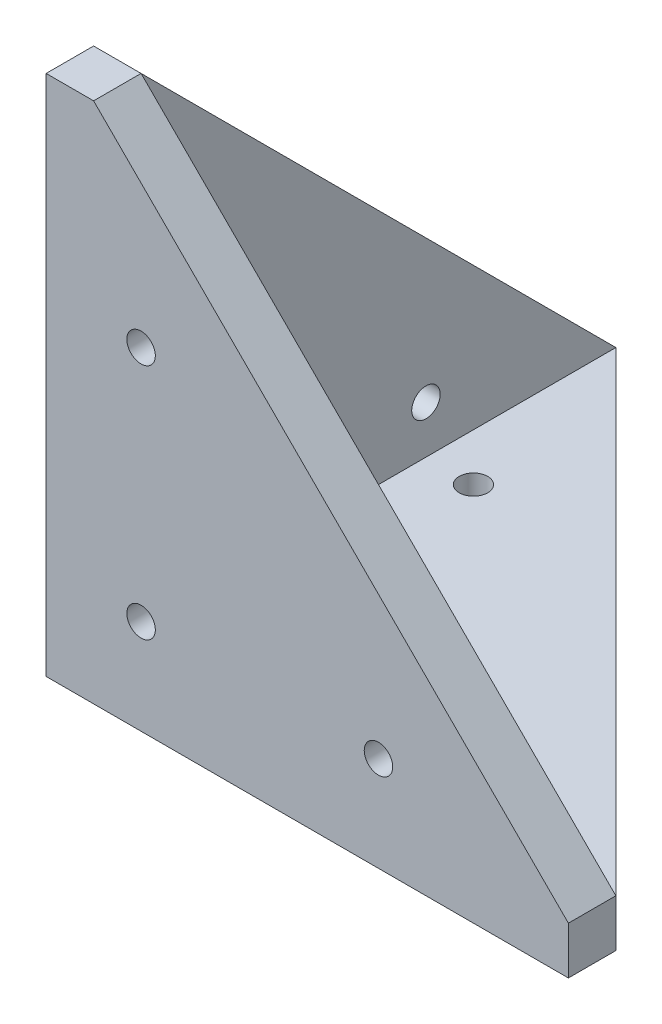
SolidWorks part; units mm, degrees
ref_plane "前视基准面" through (0, 0, 0) normal (0, 0, 1) x (1, 0, 0)
ref_plane "上视基准面" through (0, 0, 0) normal (0, 1, 0) x (1, 0, 0)
ref_plane "右视基准面" through (0, 0, 0) normal (1, 0, 0) x (0, 0, -1)
sketch "草图1" plane through (0, 0, 0) normal (0, 0, 1) x (1, 0, 0)
  line L5 (0, 50) -> (50, 0)
  line L6 (0, 50) -> (-5, 50)
  line L7 (-5, 50) -> (-5, -5)
  line L8 (-5, -5) -> (50, -5)
  line L9 (50, -5) -> (50, 0)
  dimension "D1" = 55
  dimension "D2" = 55
  dimension "D3" = 5
  dimension "D4" = 5
extrude "凸台-拉伸1" add sketch "草图1" along normal blind 5
sketch "草图2" plane through (0, 0, 0) normal (1, 0, 0) x (0, 0, -1)
  line L0 (0, 0) -> (50, 0)
  line L1 (50, 0) -> (0, 50)
  line L2 (0, 50) -> (0, 0)
  dimension "D1" = 50
  dimension "D2" = 50
extrude "凸台-拉伸2" add sketch "草图2" against normal blind 5 separate body
sketch "草图4" plane through (0, 0, 0) normal (0, 0, 1) x (1, 0, 0)
  line L1 (-5, 0) -> (0, 0)
  line L2 (-5, 0) -> (-5, -5)
  line L3 (-5, -5) -> (0, -5)
  line L4 (0, 0) -> (0, -5)
extrude "凸台-拉伸4" add sketch "草图4" against normal blind 50
sketch "草图7" plane through (0, -5, 0) normal (0, -1, 0) x (1, 0, 0)
  line L0 (50, 0) -> (0, 0)
  line L1 (0, 0) -> (0, -50)
  line L2 (0, -50) -> (50, 0)
  dimension "D1" = 50
extrude "凸台-拉伸13" add sketch "草图7" against normal blind 5
sketch "草图8" plane through (0, 0, 0) normal (1, 0, 0) x (0, 0, -1)
  line L0 (0, 0) -> (50, 0) construction
  line L2 (5, 30) -> (5, 5) construction
  line L3 (5, 5) -> (30, 5) construction
  line L5 (5, 30) -> (30, 5) construction
  line L7 (0, 0) -> (0, 50) construction
  circle A0 centre (5, 30) radius 1.5
  circle A1 centre (5, 5) radius 1.4
  circle A2 centre (30, 5) radius 1.5
  point P0 (18.9005, 16.0995)
  dimension "D1" = 25
  dimension "D2" = 25
  dimension "D3" = 5
  dimension "D4" = 5
extrude "切除-拉伸1" cut sketch "草图8" against normal through all
sketch "草图9" plane through (0, 0, 0) normal (0, 0, -1) x (-1, 0, 0)
  line L0 (0, 0) -> (0, 50) construction
  line L1 (-30, 5) -> (-5, 5) construction
  line L4 (-5, 5) -> (-5, 30) construction
  line L5 (-30, 5) -> (-5, 30) construction
  line L7 (-50, 0) -> (0, 0) construction
  circle A0 centre (-5, 30) radius 1.5
  circle A1 centre (-5, 5) radius 1.5
  circle A2 centre (-30, 5) radius 1.5
  point P0 (-20.4255, 14.5745)
  dimension "D1" = 25
  dimension "D2" = 25
  dimension "D3" = 5
  dimension "D4" = 5
extrude "切除-拉伸2" cut sketch "草图9" against normal through all
sketch "草图10" plane through (0, 0, 0) normal (0, 1, 0) x (1, 0, 0)
  line L0 (50, 0) -> (0, 0) construction
  line L1 (5, 5) -> (30, 5) construction
  line L2 (5, 5) -> (5, 30) construction
  line L5 (0, 50) -> (0, 0) construction
  circle A0 centre (5, 30) radius 1.5
  circle A1 centre (5, 5) radius 1.5
  circle A2 centre (30, 5) radius 1.5
  dimension "D1" = 25
  dimension "D2" = 25
  dimension "D3" = 5
  dimension "D4" = 5
extrude "切除-拉伸3" cut sketch "草图10" against normal through all
